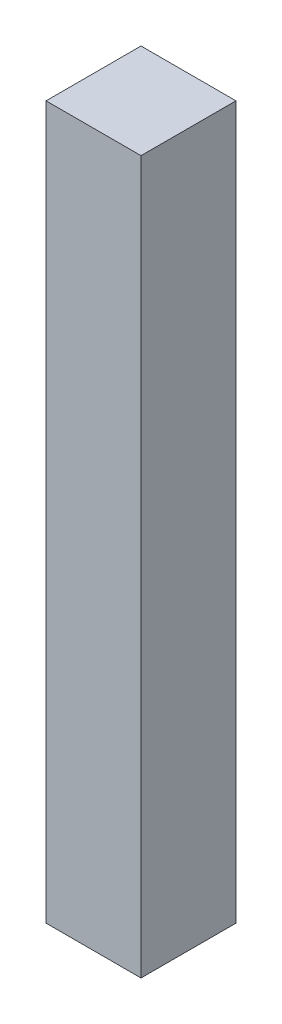
SolidWorks part; units mm, degrees
ref_plane "Front Plane" through (0, 0, 0) normal (0, 0, 1) x (1, 0, 0)
ref_plane "Top Plane" through (0, 0, 0) normal (0, 1, 0) x (1, 0, 0)
ref_plane "Right Plane" through (0, 0, 0) normal (1, 0, 0) x (0, 0, -1)
sketch "Sketch1" plane through (0, 0, 0) normal (0, 1, 0) x (1, 0, 0)
  line L1 (-10, 10) -> (10, 10)
  line L2 (-10, 10) -> (-10, -10)
  line L3 (-10, -10) -> (10, -10)
  line L4 (10, 10) -> (10, -10)
  dimension "D1" = 20
  dimension "D2" = 20
  dimension "D3" = 10
  dimension "D4" = 10
extrude "Extrude1" add sketch "Sketch1" along normal blind 150
